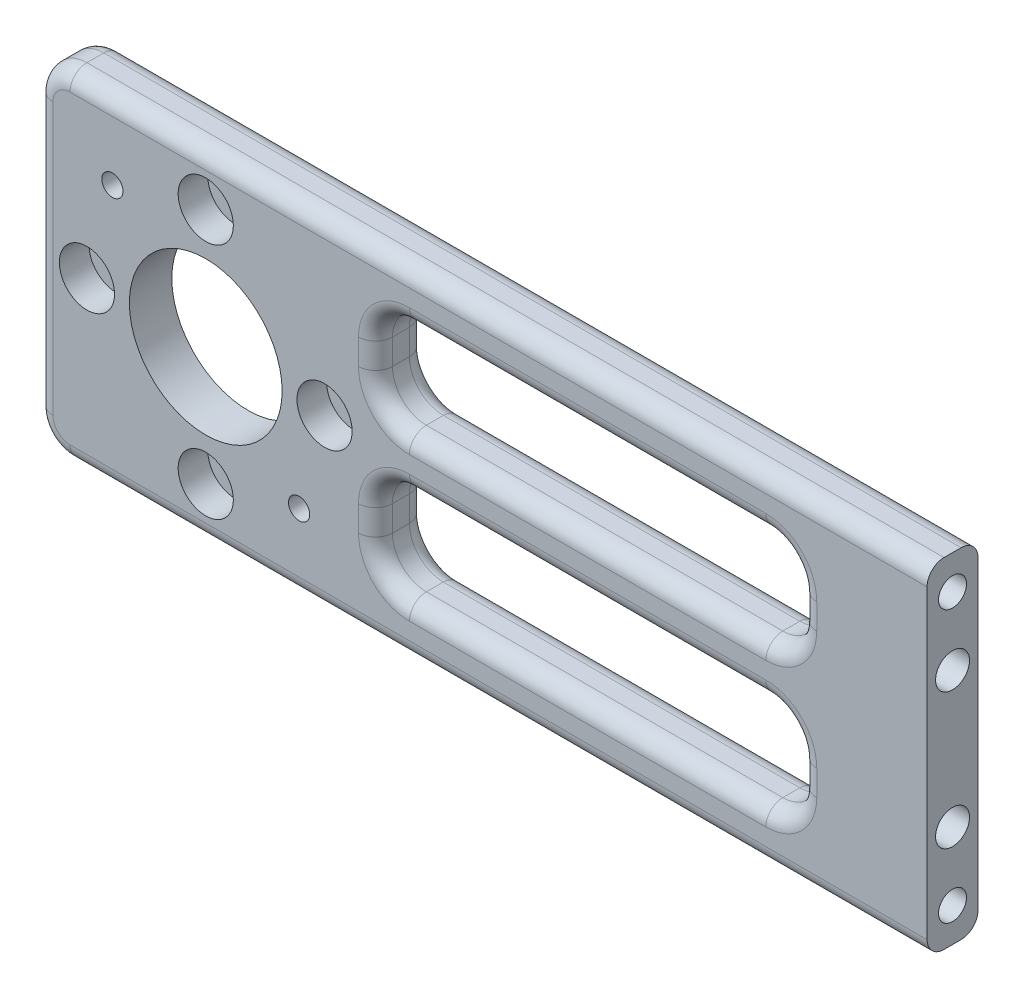
SolidWorks part; units mm, degrees
ref_plane "Face" through (0, 0, 0) normal (0, 0, 1) x (1, 0, 0)
ref_plane "Dessus" through (0, 0, 0) normal (0, 1, 0) x (1, 0, 0)
ref_plane "Droite" through (0, 0, 0) normal (1, 0, 0) x (0, 0, -1)
sketch "Esquisse1" plane through (0, 0, 0) normal (0, 0, 1) x (1, 0, 0)
  line L1 (-16, 20) -> (85, 20)
  line L2 (-20, 16) -> (-20, -16)
  line L3 (-16, -20) -> (85, -20)
  line L4 (85, 20) -> (85, -20)
  arc A0 (-16, -20) -> (-20, -16) centre (-16, -16) cw
  arc A1 (-20, 16) -> (-16, 20) centre (-16, 16) cw
  circle A2 centre (0, 0) radius 9
  point P7 (-20, -20)
  point P10 (-20, 20)
  dimension "D5" = 4
  dimension "D6" = 18
  dimension "D1" = 20
  dimension "D2" = 40
  dimension "D3" = 20
  dimension "D4" = 85
extrude "Boss.-Extru.1" add sketch "Esquisse1" along normal blind 6
hole_wizard "Trou taraudé M31" positions "Esquisse4" profile "Esquisse3" tap size "M3" standard "Iso" end condition through all
sketch "Esquisse4" plane through (0, 0, 6) normal (0, 0, 1) x (1, 0, 0)
  circle A0 centre (0, 0) radius 9 construction
  point P0 (-11, 11)
  point P2 (11, -11)
  dimension "D1" = 11
  dimension "D2" = 11
  dimension "D3" = 11
  dimension "D4" = 11
sketch "Esquisse3" plane through (-11, 11, 6) normal (1, 0, 0) x (0, -1, 0)
  line L0 (0, 0) -> (0, 6)
  line L1 (0, 6) -> (1.25, 6)
  line L2 (1.25, 6) -> (1.25, 0)
  line L5 (1.25, 0) -> (0, 0)
  line L11 (0, -6.35) -> (0, 107.95) construction
  dimension "Diamètre du trou pour taraudage jusqu'au prochain" = 2.5
  dimension "Profondeur du trou pour taraudage jusqu'au prochain" = 6
cosmetic thread "Filetage de perçage1" parameters "D2"=3
cosmetic thread "Filetage de perçage2" parameters "D2"=3
hole_wizard "Diamètre du perçage Ø4.0 (4)1" positions "Esquisse6" profile "Esquisse5" hole size "Ø4.0" standard "Din"
sketch "Esquisse6" plane through (85, 0, 0) normal (1, 0, 0) x (0, 0, -1)
  line L1 (0, -20) -> (0, 20) construction
  point P0 (-3, 8)
  point P2 (-3, -8)
  point P9 (0, 0)
  point P12 (0, 0)
  dimension "D1" = 8
  dimension "D2" = 8
  dimension "D3" = 3
  dimension "D4" = 3
sketch "Esquisse5" plane through (85, 8, 3) normal (0, 1, 0) x (0, 0, -1)
  line L0 (0, 0) -> (0, 6.2017)
  line L1 (0, 6.2017) -> (2, 5)
  line L2 (2, 5) -> (2, 0)
  line L5 (2, 0) -> (0, 0)
  line L10 (0, 6.2017) -> (-2, 5) construction
  line L11 (0, -6.35) -> (0, 107.95) construction
  dimension "Diamètre du perçage" = 4
  dimension "Profondeur du perçage" = 5
  dimension "Angle de pointe" = 118
hole_wizard "Trou taraudé M41" positions "Esquisse8" profile "Esquisse7" tap size "M4" standard "Iso"
sketch "Esquisse8" plane through (85, 0, 0) normal (1, 0, 0) x (0, 0, -1)
  line L0 (0, -20) -> (0, 20) construction
  point P0 (-3, 16)
  point P2 (0, 0)
  point P12 (0, 0)
  point P13 (-3, -16)
  point P15 (0, 0)
  dimension "D1" = 16
  dimension "D2" = 3
  dimension "D3" = 3
  dimension "D4" = 16
sketch "Esquisse7" plane through (85, 16, 3) normal (0, 1, 0) x (0, 0, -1)
  line L0 (0, 0) -> (0, 12.4914)
  line L1 (0, 12.4914) -> (1.65, 11.5)
  line L2 (1.65, 11.5) -> (1.65, 0)
  line L5 (1.65, 0) -> (0, 0)
  line L10 (0, 12.4914) -> (-1.65, 11.5) construction
  line L11 (0, -6.35) -> (0, 107.95) construction
  dimension "Diamètre du trou pour taraudage" = 3.3
  dimension "Profondeur du trou pour taraudage" = 11.5
  dimension "Angle de pointe" = 118
cosmetic thread "Filetage de perçage3" parameters "D1"=8, "D2"=4
cosmetic thread "Filetage de perçage4" parameters "D1"=8, "D2"=4
hole_wizard "Chambrage pour vis à tête hexagonale M31" positions "Esquisse12" profile "Esquisse11" counterbore size "M3" standard "Iso" end condition through all
sketch "Esquisse12" plane through (0, 0, 6) normal (0, 0, 1) x (1, 0, 0)
  circle A1 centre (0, 0) radius 14 construction
  point P46 (0, 14)
  point P48 (14, 0)
  point P50 (0, -14)
  point P52 (-14, 0)
  dimension "D1" = 28
sketch "Esquisse11" plane through (0, 14, 6) normal (1, 0, 0) x (0, -1, 0)
  line L0 (0, 0) -> (0, 6)
  line L1 (0, 6) -> (1.6, 6)
  line L3 (1.6, 6) -> (1.6, 3.5)
  line L4 (1.6, 3.5) -> (3.25, 3.5)
  line L5 (3.25, 3.5) -> (3.25, 0)
  line L7 (3.25, 0) -> (0, 0)
  line L11 (0, -6.35) -> (0, 107.95) construction
  dimension "Diamètre du perçage jusqu'au prochain" = 3.2
  dimension "Profondeur du perçage jusqu'au prochain" = 6
  dimension "Diamètre du chambrage" = 6.5
  dimension "Profondeur du chambrage" = 3.5
sketch "Esquisse13" plane through (0, 0, 6) normal (0, 0, 1) x (1, 0, 0)
  line L0 (20, 8.5) -> (20, -8.5) construction
  line L1 (20, 10) -> (20, 7)
  line L2 (20, 8.5) -> (70, 8.5) construction
  line L3 (85, -20) -> (85, 20) construction
  line L4 (20, -8.5) -> (70, -8.5) construction
  line L5 (70, 8.5) -> (70, -8.5) construction
  line L6 (24, 3) -> (66, 3)
  line L7 (70, 7) -> (70, 10)
  line L8 (66, 14) -> (24, 14)
  line L9 (20, -7) -> (20, -10)
  line L10 (24, -14) -> (66, -14)
  line L11 (70, -7) -> (70, -10)
  line L12 (66, -3) -> (24, -3)
  circle A0 centre (0, 0) radius 9 construction
  arc A1 (70, 7) -> (66, 3) centre (66, 7) cw
  arc A2 (70, 10) -> (66, 14) centre (66, 10) ccw
  arc A3 (20, 7) -> (24, 3) centre (24, 7) ccw
  arc A4 (20, 10) -> (24, 14) centre (24, 10) cw
  arc A5 (66, -14) -> (70, -10) centre (66, -10) ccw
  arc A6 (70, -7) -> (66, -3) centre (66, -7) ccw
  arc A7 (20, -10) -> (24, -14) centre (24, -10) ccw
  arc A8 (20, -7) -> (24, -3) centre (24, -7) cw
  point P15 (70, 3)
  point P20 (20, 3)
  point P31 (70, -3)
  point P36 (20, -3)
  dimension "D7" = 4
  dimension "D10" = 4
  dimension "D1" = 20
  dimension "D2" = 8.5
  dimension "D3" = 8.5
  dimension "D4" = 15
  dimension "D5" = 5.5
  dimension "D6" = 5.5
  dimension "D8" = 5.5
  dimension "D9" = 5.5
extrude "Enlèv. mat.-Extru.1" cut sketch "Esquisse13" against normal up to next
fillet "Congé1" radius 2 42 edges at (34.5, 20, 6) (-18.8284, 18.8284, 6) (-20, 0, 6) (-18.8284, -18.8284, 6) (34.5, -20, 6) (34.5, -20, 0) (-18.8284, -18.8284, 0) (-20, 0, 0) (-18.8284, 18.8284, 0) (34.5, 20, 0) (68.8284, 12.8284, 6) (70, 8.5, 6) (68.8284, 4.1716, 6) (45, 3, 6) (21.1716, 4.1716, 6) (20, 8.5, 6) (21.1716, 12.8284, 6) (45, 14, 6) (45, -14, 0) (21.1716, -12.8284, 0) (20, -8.5, 0) (21.1716, -4.1716, 0) (68.8284, 12.8284, 0) (70, 8.5, 0) (68.8284, 4.1716, 0) (45, 3, 0) (21.1716, 4.1716, 0) (20, 8.5, 0) (21.1716, 12.8284, 0) (21.1716, -12.8284, 6) (20, -8.5, 6) (21.1716, -4.1716, 6) (45, -3, 6) (45, -3, 0) (45, 14, 0) (45, -14, 6) (68.8284, -4.1716, 0) (70, -8.5, 0) (68.8284, -12.8284, 0) (68.8284, -4.1716, 6) (70, -8.5, 6) (68.8284, -12.8284, 6)
sketch "Esquisse14" plane through (0, 0, 0) normal (0, 0, -1) x (-1, 0, 0)
  circle A0 centre (0, 0) radius 17.5
  dimension "D1" = 35
extrude "Enlèv. mat.-Extru.2" cut sketch "Esquisse14" against normal blind 1
